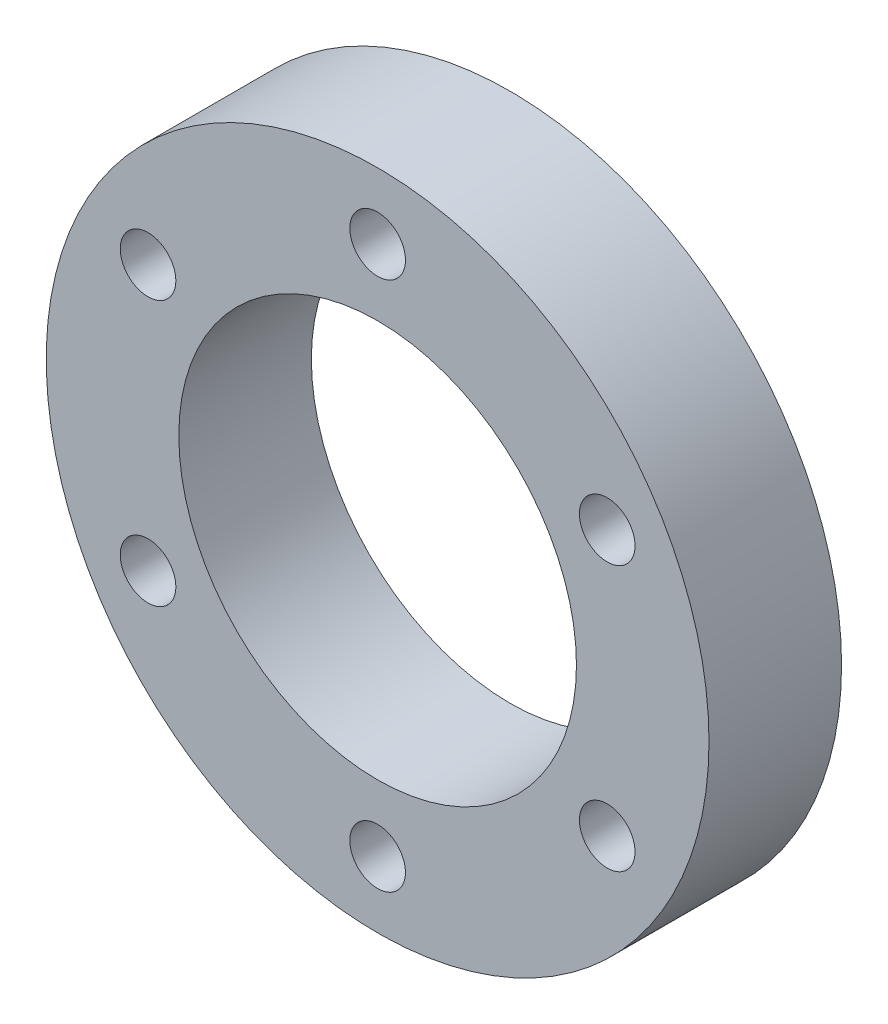
SolidWorks part; units mm, degrees
ref_plane "Front" through (0, 0, 0) normal (0, 0, 1) x (1, 0, 0)
ref_plane "Top" through (0, 0, 0) normal (0, 1, 0) x (1, 0, 0)
ref_plane "Right" through (0, 0, 0) normal (1, 0, 0) x (0, 0, -1)
sketch "Sketch1" plane through (0, 0, 0) normal (0, 0, 1) x (1, 0, 0)
  circle A0 centre (0, 0) radius 31.75
  circle A1 centre (0, 0) radius 19.05
  dimension "D1" = 38.1
  dimension "D2" = 63.5
extrude "Boss-Extrude1" add sketch "Sketch1" along normal blind 12.7
sketch "Sketch2" plane through (0, 0, 12.7) normal (0, 0, 1) x (1, 0, 0)
  line L0 (0, 31.75) -> (0, 0) construction
  circle A0 centre (0, 0) radius 31.75 construction
  circle A1 centre (0, 25.4) radius 2.665
  circle A2 centre (21.997, 12.7) radius 2.665
  circle A3 centre (21.997, -12.7) radius 2.665
  circle A4 centre (0, -25.4) radius 2.665
  circle A5 centre (-21.997, -12.7) radius 2.665
  circle A6 centre (-21.997, 12.7) radius 2.665
  point P13 (0, 0)
  dimension "D1" = 25.4
  dimension "D2" = 5.33
  dimension "D3" = 6
extrude "Cut-Extrude1" cut sketch "Sketch2" against normal up to next
